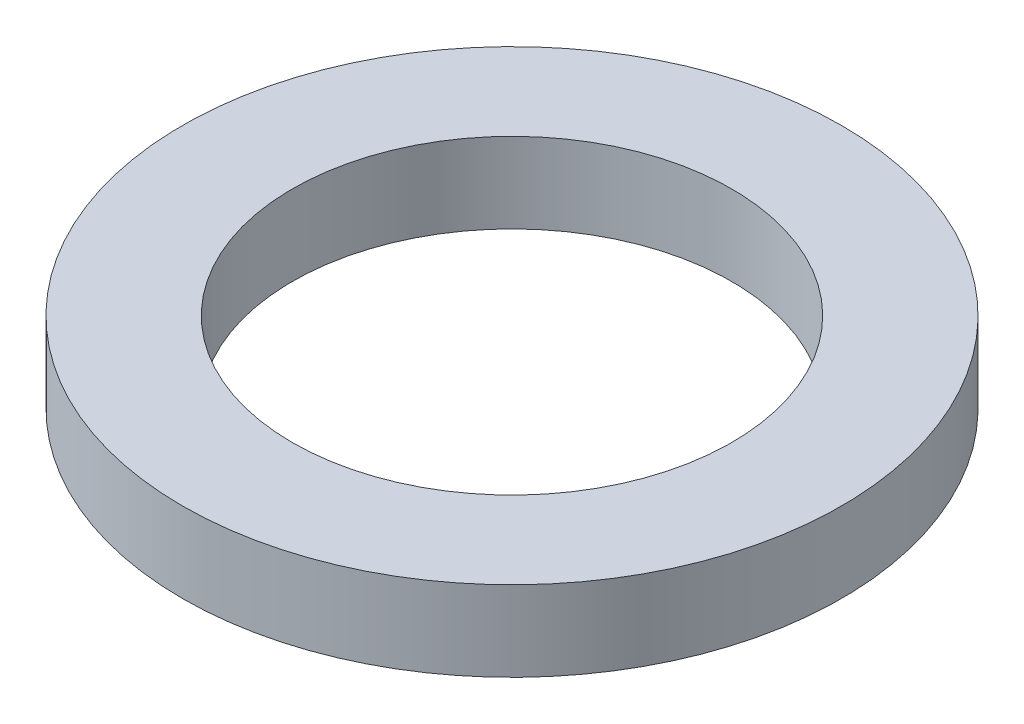
SolidWorks part; units mm, degrees
ref_plane "Alzado" through (0, 0, 0) normal (0, 0, 1) x (1, 0, 0)
ref_plane "Planta" through (0, 0, 0) normal (0, 1, 0) x (1, 0, 0)
ref_plane "Vista lateral" through (0, 0, 0) normal (1, 0, 0) x (0, 0, -1)
sketch "Croquis1" plane through (0, 0, 0) normal (0, 1, 0) x (1, 0, 0)
  circle A0 centre (0, 0) radius 5
  circle A1 centre (0, 0) radius 7.5
  dimension "D1" = 10
  dimension "D2" = 15
extrude "Saliente-Extruir1" add sketch "Croquis1" along normal blind 1.825
